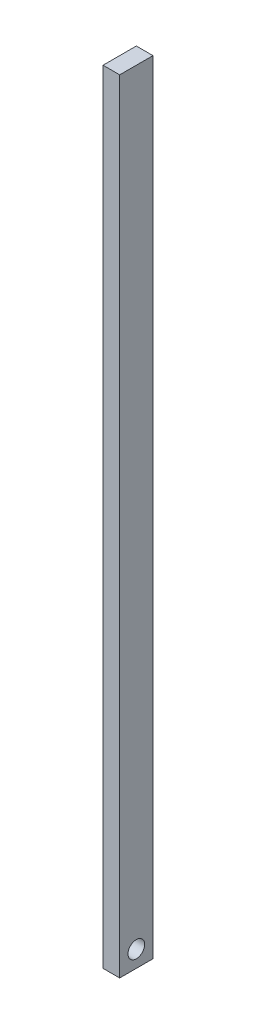
SolidWorks part; units mm, degrees
ref_plane "Front Plane" through (0, 0, 0) normal (0, 0, 1) x (1, 0, 0)
ref_plane "Top Plane" through (0, 0, 0) normal (0, 1, 0) x (1, 0, 0)
ref_plane "Right Plane" through (0, 0, 0) normal (1, 0, 0) x (0, 0, -1)
sketch "Sketch1" plane through (0, 0, 0) normal (0, 1, 0) x (1, 0, 0)
  line L1 (0, 0) -> (25.4, 0)
  line L2 (0, 0) -> (0, 50.8)
  line L3 (0, 50.8) -> (25.4, 50.8)
  line L4 (25.4, 0) -> (25.4, 50.8)
  dimension "D1" = 25.4
  dimension "D2" = 50.8
extrude "Boss-Extrude1" add sketch "Sketch1" along normal blind 1193.8
sketch "Sketch2" plane through (25.4, 0, 0) normal (1, 0, 0) x (0, 0, -1)
  line L0 (25.4, 0) -> (25.4, 120.9248) construction
  line L1 (0, 0) -> (50.8, 0) construction
  circle A0 centre (25.4, 25.4) radius 12.7
  dimension "D2" = 25.4
  dimension "D1" = 25.4
extrude "Cut-Extrude1" cut sketch "Sketch2" against normal blind 1193.8
